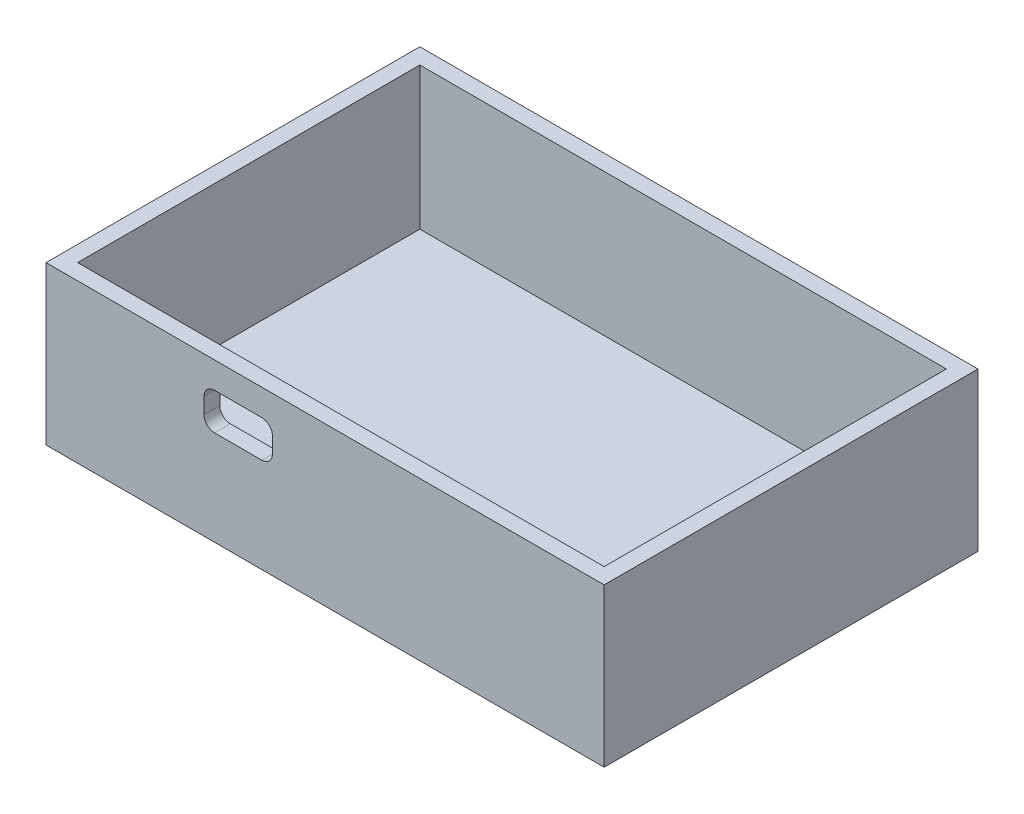
SolidWorks part; units mm, degrees
ref_plane "Front Plane" through (0, 0, 0) normal (0, 0, 1) x (1, 0, 0)
ref_plane "Top Plane" through (0, 0, 0) normal (0, 1, 0) x (1, 0, 0)
ref_plane "Right Plane" through (0, 0, 0) normal (1, 0, 0) x (0, 0, -1)
sketch "Sketch1" plane through (0, 0, 0) normal (0, 1, 0) x (1, 0, 0)
  line L5 (-54.8221, 39.359) -> (51.1779, 39.359)
  line L6 (-54.8221, 39.359) -> (-54.8221, -31.641)
  line L7 (-54.8221, -31.641) -> (51.1779, -31.641)
  line L8 (51.1779, 39.359) -> (51.1779, -31.641)
  point P5 (0, 0)
  dimension "D1" = 71
  dimension "D2" = 106
extrude "Boss-Extrude1" add sketch "Sketch1" along normal blind 30
sketch "Sketch2" plane through (0, 30, 0) normal (0, 1, 0) x (1, 0, 0)
  line L0 (51.1779, -31.641) -> (51.1779, 39.359) construction
  line L1 (-51.8221, 36.359) -> (48.1779, 36.359)
  line L2 (-51.8221, 36.359) -> (-51.8221, -28.641)
  line L3 (-51.8221, -28.641) -> (48.1779, -28.641)
  line L4 (48.1779, 36.359) -> (48.1779, -28.641)
  line L5 (-54.8221, -31.641) -> (51.1779, -31.641) construction
  line L6 (-54.8221, 39.359) -> (-54.8221, -31.641) construction
  line L7 (51.1779, 39.359) -> (-54.8221, 39.359) construction
  dimension "D1" = 3
  dimension "D2" = 3
  dimension "D3" = 3
  dimension "D4" = 3
extrude "Cut-Extrude1" cut sketch "Sketch2" against normal blind 27
sketch "Sketch3" plane through (0, 0, 28.641) normal (0, 0, -1) x (-1, 0, 0)
  line L0 (51.8221, 3) -> (51.8221, 30) construction
  line L1 (24.8221, 25) -> (11.8221, 25)
  line L2 (24.8221, 25) -> (24.8221, 18)
  line L3 (24.8221, 18) -> (11.8221, 18)
  line L4 (11.8221, 25) -> (11.8221, 18)
  line L5 (51.8221, 3) -> (-48.1779, 3) construction
  dimension "D1" = 27
  dimension "D2" = 40
  dimension "D3" = 22
  dimension "D4" = 15
extrude "Cut-Extrude2" cut sketch "Sketch3" against normal through all
fillet "Fillet1" radius 2 4 edges at (-11.8221, 18, 30.141) (-11.8221, 25, 30.141) (-24.8221, 25, 30.141) (-24.8221, 18, 30.141)
